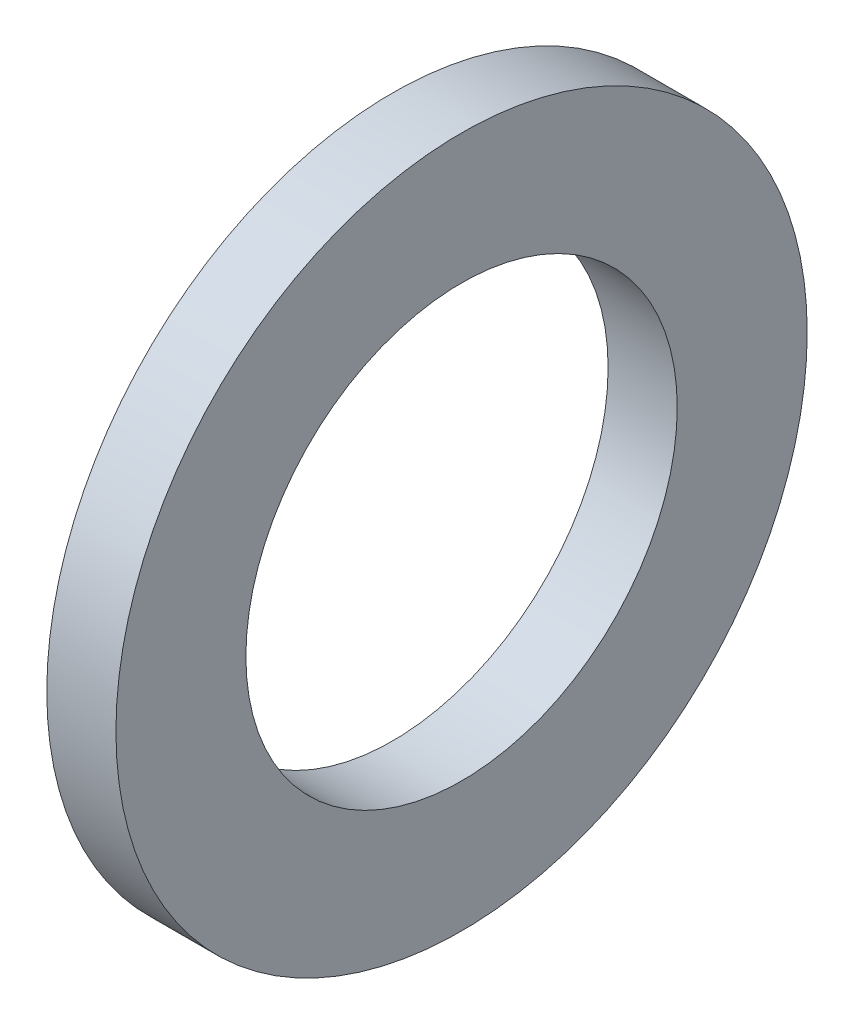
SolidWorks part; units mm, degrees
material "PET"
ref_plane "Front Plane" through (0, 0, 0) normal (0, 0, 1) x (1, 0, 0)
ref_plane "Top Plane" through (0, 0, 0) normal (0, 1, 0) x (1, 0, 0)
ref_plane "Right Plane" through (0, 0, 0) normal (1, 0, 0) x (0, 0, -1)
sketch "Sketch1" plane through (0, 0, 0) normal (1, 0, 0) x (0, 0, -1)
  circle A0 centre (0, 0) radius 7.9375
  circle A1 centre (0, 0) radius 4.953
  dimension "D1" = 9.906
  dimension "D2" = 15.875
extrude "Boss-Extrude1" add sketch "Sketch1" along normal blind 1.5875
